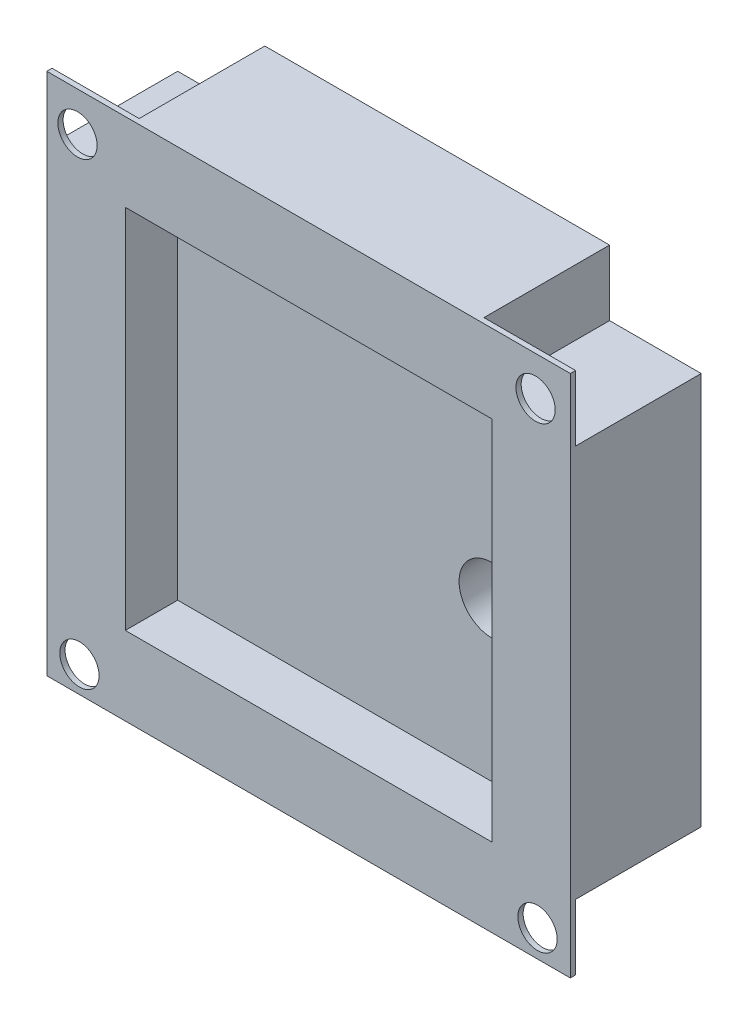
SolidWorks part; units mm, degrees
ref_plane "Front Plane" through (0, 0, 0) normal (0, 0, 1) x (1, 0, 0)
ref_plane "Top Plane" through (0, 0, 0) normal (0, 1, 0) x (1, 0, 0)
ref_plane "Right Plane" through (0, 0, 0) normal (1, 0, 0) x (0, 0, -1)
sketch "Sketch1" plane through (0, 0, 0) normal (0, 0, 1) x (1, 0, 0)
  line L0 (0, 0) -> (50.8, 0)
  line L1 (50.8, 0) -> (50.8, 50.8)
  line L2 (50.8, 50.8) -> (0, 50.8)
  line L3 (0, 50.8) -> (0, 0)
  dimension "D1" = 50.8
  dimension "D2" = 50.8
extrude "Boss-Extrude1" add sketch "Sketch1" along normal blind 12.7
shell "Shell1" thickness 7.62
sketch "Sketch3" plane through (0, 0, 0) normal (0, 0, -1) x (-1, 0, 0)
  line L2 (-50.8, 50.8) -> (-41.91, 50.8)
  line L4 (-50.8, 50.8) -> (-50.8, 44.45)
  line L5 (-50.8, 44.45) -> (-41.91, 44.45)
  line L7 (-41.91, 50.8) -> (-41.91, 44.45)
  line L9 (-50.8, 0) -> (-41.91, 0)
  line L10 (-50.8, 0) -> (-50.8, 6.35)
  line L11 (-50.8, 6.35) -> (-41.91, 6.35)
  line L12 (-41.91, 0) -> (-41.91, 6.35)
  line L13 (0, 0) -> (-8.89, 0)
  line L14 (0, 0) -> (0, 6.35)
  line L15 (0, 6.35) -> (-8.89, 6.35)
  line L16 (-8.89, 0) -> (-8.89, 6.35)
  line L17 (0, 50.8) -> (-8.4551, 50.8)
  line L18 (0, 50.8) -> (0, 44.45)
  line L19 (0, 44.45) -> (-8.4551, 44.45)
  line L20 (-8.4551, 50.8) -> (-8.4551, 44.45)
  dimension "D1" = 8.89
  dimension "D2" = 6.35
  dimension "D3" = 6.35
  dimension "D4" = 6.35
  dimension "D5" = 8.89
  dimension "D6" = 8.89
  dimension "D7" = 6.35
extrude "Cut-Extrude2" cut sketch "Sketch3" against normal blind 12.192
sketch "Sketch4" plane through (0, 0, 12.7) normal (0, 0, 1) x (1, 0, 0)
  line L0 (25.4, 43.18) -> (25.4, 50.8) construction
  line L1 (43.18, 43.18) -> (7.62, 43.18) construction
  line L2 (50.8, 50.8) -> (0, 50.8) construction
  line L3 (25.4, 50.8) -> (25.4, 0) construction
  line L4 (0, 0) -> (50.8, 0) construction
  line L5 (0, 25.4) -> (50.8, 25.4) construction
  line L6 (0, 50.8) -> (0, 0) construction
  line L7 (50.8, 0) -> (50.8, 50.8) construction
  line L8 (25.4, 46.99) -> (0, 46.99) construction
  line L9 (25.4, 46.99) -> (50.8, 46.99) construction
  line L10 (2.9778, 46.99) -> (2.9778, 0) construction
  line L11 (3.1667, 2.54) -> (50.8, 2.54) construction
  circle A0 centre (2.9778, 46.99) radius 1.905
  circle A1 centre (47.4278, 47.0018) radius 1.905
  circle A2 centre (3.1667, 2.54) radius 1.905
  circle A3 centre (47.6167, 2.6178) radius 1.905
  dimension "D1" = 3.81
  dimension "D2" = 44.45
  dimension "D3" = 44.45
  dimension "D4" = 44.45
  dimension "D5" = 2.9778
  dimension "D6" = 3.3722
  dimension "D7" = 3.1667
  dimension "D8" = 2.54
  dimension "D9" = 2.6178
extrude "Cut-Extrude3" cut sketch "Sketch4" against normal blind 20.574
sketch "Sketch5" plane through (0, 0, 0) normal (0, 0, -1) x (-1, 0, 0)
  line L0 (-50.8, 25.4) -> (0, 25.4) construction
  line L1 (-50.8, 6.35) -> (-50.8, 44.45) construction
  line L2 (0, 44.45) -> (0, 6.35) construction
  line L3 (-25.1826, 50.8) -> (-25.1826, -5.0905) construction
  line L5 (-41.91, 50.8) -> (-8.4551, 50.8) construction
sketch "Sketch6" plane through (0, 0, 0) normal (0, 0, -1) x (-1, 0, 0)
  line L0 (-41.91, 50.8) -> (-8.4551, 50.8) construction
  line L1 (-50.8, 6.35) -> (-50.8, 44.45) construction
  circle A0 centre (-38.1, 22.86) radius 3.175
  dimension "D1" = 6.35
  dimension "D3" = 27.94
  dimension "D2" = 12.7
extrude "Cut-Extrude5" cut sketch "Sketch6" against normal blind 8.89
